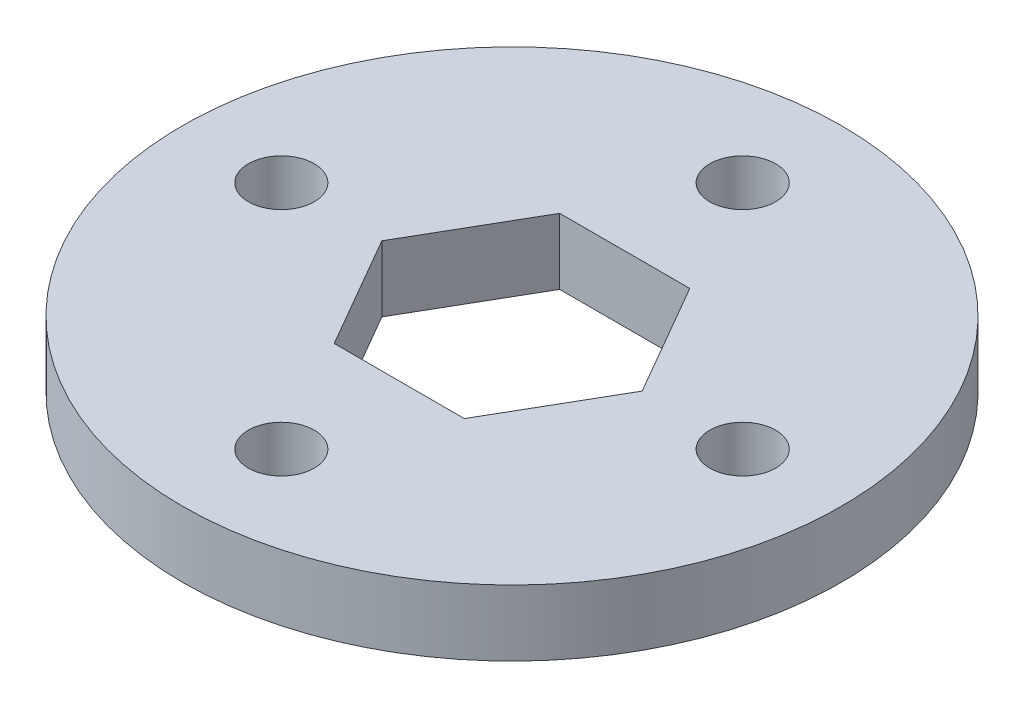
SolidWorks part; units mm, degrees
ref_plane "Front Plane" through (0, 0, 0) normal (0, 0, 1) x (1, 0, 0)
ref_plane "Top Plane" through (0, 0, 0) normal (0, 1, 0) x (1, 0, 0)
ref_plane "Right Plane" through (0, 0, 0) normal (1, 0, 0) x (0, 0, -1)
sketch "Sketch1" plane through (0, 0, 0) normal (0, 1, 0) x (1, 0, 0)
  line L1 (-9.8727, 0) -> (-4.9363, -8.55)
  line L2 (-4.9363, -8.55) -> (4.9363, -8.55)
  line L3 (4.9363, -8.55) -> (9.8727, 0)
  line L4 (9.8727, 0) -> (4.9363, 8.55)
  line L5 (4.9363, 8.55) -> (-4.9363, 8.55)
  line L6 (-4.9363, 8.55) -> (-9.8727, 0)
  circle A0 centre (0, 0) radius 8.55 construction
  circle A1 centre (0, 0) radius 25
extrude "Boss-Extrude1" add sketch "Sketch1" along normal blind 5
sketch "Sketch2" plane through (0, 5, 0) normal (0, 1, 0) x (1, 0, 0)
  circle A0 centre (0, 0) radius 17.5
sketch "Sketch3" plane through (0, 5, 0) normal (0, 1, 0) x (1, 0, 0)
  circle A0 centre (0, 17.5) radius 2.5
  circle A1 centre (0, 0) radius 17.5 construction
  circle A2 centre (17.5, 0) radius 2.5
  circle A3 centre (0, -17.5) radius 2.5
  circle A4 centre (-17.5, 0) radius 2.5
  point P13 (0, 0)
  dimension "D1" = 4
extrude "Cut-Extrude1" cut sketch "Sketch3" against normal blind 18
